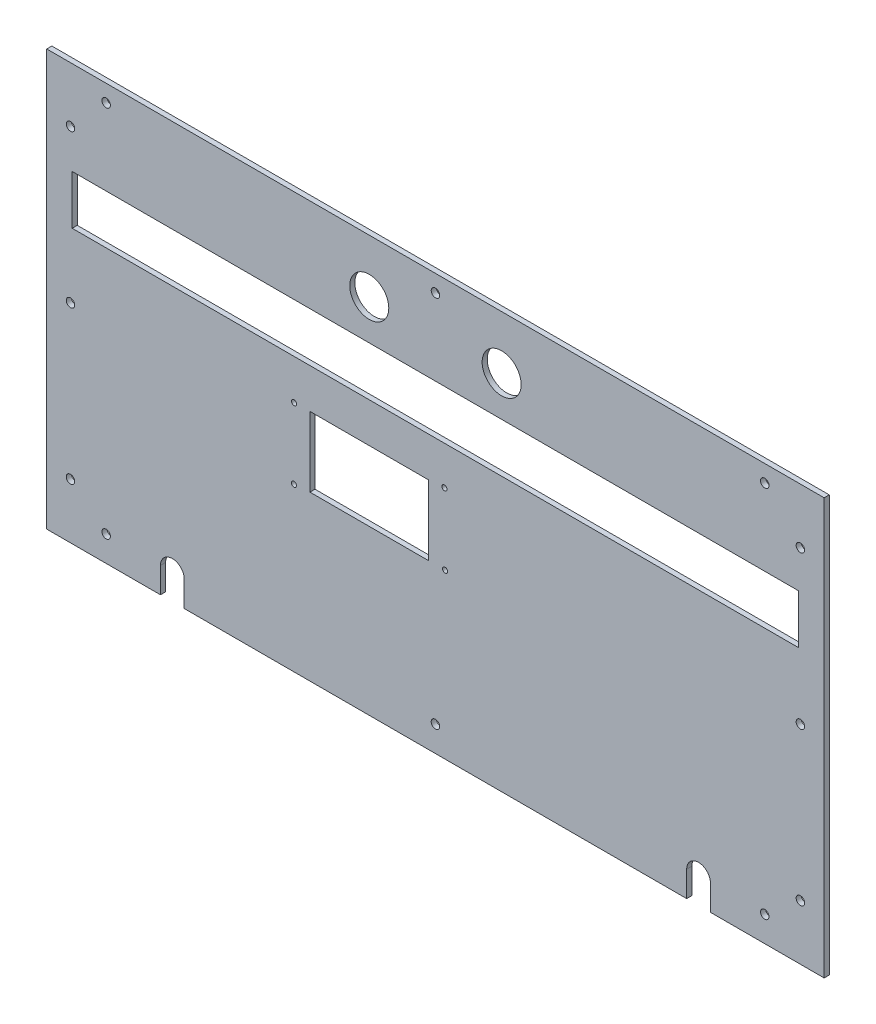
SolidWorks part; units mm, degrees
material "1345 Alloy"
ref_plane "Front Plane" through (0, 0, 0) normal (0, 0, 1) x (1, 0, 0)
ref_plane "Top Plane" through (0, 0, 0) normal (0, 1, 0) x (1, 0, 0)
ref_plane "Right Plane" through (0, 0, 0) normal (1, 0, 0) x (0, 0, -1)
sketch "Sketch1" plane through (0, 0, 0) normal (0, 0, 1) x (1, 0, 0)
  line L1 (-229, 122.5) -> (229, 122.5)
  line L2 (-229, 122.5) -> (-229, -122.5)
  line L3 (-229, -122.5) -> (229, -122.5)
  line L4 (229, 122.5) -> (229, -122.5)
  line L5 (-229, 122.5) -> (229, -122.5) construction
  line L6 (-229, -122.5) -> (229, 122.5) construction
  point P0 (0, 0)
  dimension "D1" = 458
  dimension "D2" = 245
extrude "Boss-Extrude1" add sketch "Sketch1" along normal blind 3
sketch "Sketch2" plane through (0, 0, 3) normal (0, 0, 1) x (1, 0, 0)
  line L0 (-229, -122.5) -> (-155, -122.5) construction
  line L2 (-155, -122.5) -> (-155, -107.5) construction
  line L3 (-155, -107.5) -> (-155, -122.5) construction
  line L6 (-148, -107.5) -> (-148, -122.5)
  line L11 (-162, -107.5) -> (-162, -122.5)
  line L12 (155, -122.5) -> (229, -122.5) construction
  line L13 (155, -107.5) -> (155, -122.5) construction
  line L14 (162, -107.5) -> (162, -122.5)
  line L15 (148, -107.5) -> (148, -122.5)
  line L16 (-155, -107.5) -> (155, -107.5) construction
  arc A4 (-148, -107.5) -> (-162, -107.5) centre (-155, -107.5) ccw
  arc A5 (-162, -122.5) -> (-148, -122.5) centre (-155, -122.5) ccw
  arc A6 (162, -107.5) -> (148, -107.5) centre (155, -107.5) ccw
  arc A7 (148, -122.5) -> (162, -122.5) centre (155, -122.5) ccw
  point P4 (-155, -115)
  point P13 (155, -115)
  dimension "D3" = 7
  dimension "D5" = 7
  dimension "D1" = 74
  dimension "D2" = 15
  dimension "D4" = 15
  dimension "D6" = 74
extrude "Cut-Extrude1" cut sketch "Sketch2" against normal through all
sketch "Sketch3" plane through (0, 0, 3) normal (0, 0, 1) x (1, 0, 0)
  line L19 (194, 112.5) -> (194, -107.5) construction
  line L20 (-215, 0) -> (-215, 90) construction
  line L21 (-215, 0) -> (-215, -90) construction
  line L25 (229, 0) -> (215, 0) construction
  line L26 (0, 112.5) -> (-194, 112.5) construction
  line L27 (-194, 112.5) -> (-194, -107.5) construction
  line L31 (215, 0) -> (215, 90) construction
  line L32 (215, 0) -> (215, -90) construction
  line L33 (0, 112.5) -> (194, 112.5) construction
  line L34 (0, 0) -> (0, 112.5) construction
  line L35 (0, 0) -> (0, -107.5) construction
  line L36 (-194, -107.5) -> (0, -107.5) construction
  line L37 (0, -107.5) -> (194, -107.5) construction
  line L38 (-194, 112.5) -> (-229, 112.5) construction
  line L39 (-229, 112.5) -> (-229, 122.5) construction
  circle A12 centre (-194, 112.5) radius 2.5
  circle A13 centre (-194, -107.5) radius 2.5
  circle A14 centre (194, -107.5) radius 2.5
  circle A15 centre (194, 112.5) radius 2.5
  circle A16 centre (-215, 0) radius 2.5
  circle A17 centre (-215, -90) radius 2.5
  circle A18 centre (-215, 90) radius 2.5
  circle A19 centre (215, 0) radius 2.5
  circle A20 centre (215, -90) radius 2.5
  circle A21 centre (215, 90) radius 2.5
  circle A22 centre (0, 112.5) radius 2.5
  circle A23 centre (0, -107.5) radius 2.5
  dimension "D3" = 5
  dimension "D6" = 90
  dimension "D9" = 5
  dimension "D12" = 90
  dimension "D15" = 5
  dimension "D16" = 194
  dimension "D17" = 194
  dimension "D2" = 5
  dimension "D4" = 5
  dimension "D5" = 5
  dimension "D8" = 5
  dimension "D10" = 5
  dimension "D14" = 5
  dimension "D7" = 90
  dimension "D11" = 14
  dimension "D13" = 90
  dimension "D18" = 194
  dimension "D19" = 194
extrude "Cut-Extrude2" cut sketch "Sketch3" against normal through all
sketch "Sketch4" plane through (0, 0, 3) normal (0, 0, 1) x (1, 0, 0)
  line L5 (0, 122.5) -> (0, 102.5) construction
  line L6 (229, 122.5) -> (-229, 122.5) construction
  line L7 (0, 102.5) -> (0, 82.5) construction
  line L8 (229, 91) -> (39, 91) construction
  line L10 (-39, 102.5) -> (-39, 122.5) construction
  line L11 (229, -122.5) -> (229, 122.5) construction
  line L12 (-229, 91) -> (-39, 91) construction
  line L13 (-229, 122.5) -> (-229, -122.5) construction
  line L14 (-39, 91) -> (0, 91) construction
  circle A1 centre (-39, 91) radius 11.5
  circle A2 centre (39, 91) radius 11.5
  dimension "D6" = 190
  dimension "D4" = 23
  dimension "D7" = 23
  dimension "D1" = 20
  dimension "D2" = 20
  dimension "D3" = 20
  dimension "D5" = 190
extrude "Cut-Extrude3" cut sketch "Sketch4" against normal through all
sketch "Sketch5" plane through (0, 0, 3) normal (0, 0, 1) x (1, 0, 0)
  line L0 (-229, -122) -> (-229, 53) construction
  line L1 (-229, 53) -> (229, 53) construction
  line L2 (-229, 53) -> (-229, 67.5) construction
  line L3 (-229, 67.5) -> (-214, 67.5) construction
  line L4 (229, 53) -> (229, 67.5) construction
  line L5 (229, 67.5) -> (214, 67.5) construction
  line L6 (214, 67.5) -> (-214, 67.5)
  line L7 (-214, 67.5) -> (-214, 38.5)
  line L8 (-214, 38.5) -> (214, 38.5)
  line L9 (214, 38.5) -> (214, 67.5)
  dimension "D1" = 175
  dimension "D2" = 14.5
  dimension "D3" = 15
  dimension "D4" = 14.5
  dimension "D5" = 15
  dimension "D6" = 29
extrude "Cut-Extrude4" cut sketch "Sketch5" against normal through all
sketch "Sketch8" plane through (0, 0, 3) normal (0, 0, 1) x (1, 0, 0)
  line L0 (-39, -5.5) -> (-39, 79.5) construction
  line L1 (-73.95, 15.1) -> (-4.05, 15.1)
  line L2 (-73.95, 15.1) -> (-73.95, -26.1)
  line L3 (-73.95, -26.1) -> (-4.05, -26.1)
  line L4 (-4.05, 15.1) -> (-4.05, -26.1)
  line L5 (-73.95, 15.1) -> (-4.05, -26.1) construction
  line L6 (-73.95, -26.1) -> (-4.05, 15.1) construction
  line L12 (5.6797, -26.0547) -> (-83.3, 14.88) construction
  line L13 (5.2962, 15.7036) -> (-83.368, -26.7379) construction
  circle A1 centre (-39, 91) radius 11.5 construction
  circle A2 centre (5.2962, 15.7036) radius 1.5
  circle A3 centre (5.6797, -26.0547) radius 1.5
  circle A4 centre (-83.3, 14.88) radius 1.5
  circle A5 centre (-83.368, -26.7379) radius 1.5
  point P0 (-39, -5.5)
  dimension "D6" = 3
  dimension "D7" = 3
  dimension "D8" = 3
  dimension "D9" = 3
  dimension "D1" = 69.9
  dimension "D2" = 41.2
  dimension "D3" = 85
  dimension "D4" = 88.6
  dimension "D5" = 41.76
extrude "Cut-Extrude5" cut sketch "Sketch8" against normal through all
